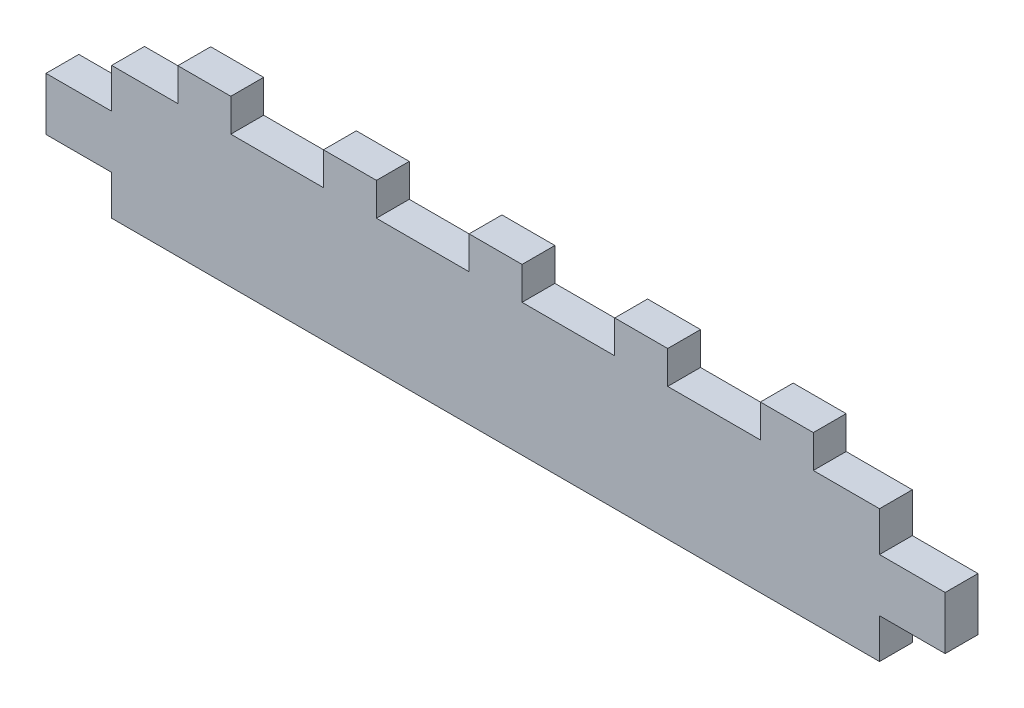
SolidWorks part; units mm, degrees
ref_plane "Front Plane" through (0, 0, 0) normal (0, 0, 1) x (1, 0, 0)
ref_plane "Top Plane" through (0, 0, 0) normal (0, 1, 0) x (1, 0, 0)
ref_plane "Right Plane" through (0, 0, 0) normal (1, 0, 0) x (0, 0, -1)
sketch "Model" plane through (0, 0, 0) normal (0, 0, 1) x (1, 0, 0)
  line L0 (145, 35) -> (145, 50)
  line L1 (-145, 0) -> (145, 0)
  line L2 (-145, 0) -> (-145, 15)
  line L3 (-145, 50) -> (-120, 50)
  line L4 (145, 0) -> (145, 15)
  line L5 (145, 15) -> (169.8, 15)
  line L6 (-145, 35) -> (-145, 50)
  line L7 (145, 35) -> (169.8, 35)
  line L8 (169.8, 15) -> (169.8, 35)
  line L9 (-145, 15) -> (-169.8, 15)
  line L10 (0, 0) -> (0, 62.4) construction
  line L11 (-145, 35) -> (-169.8, 35)
  line L12 (-169.8, 15) -> (-169.8, 35)
  line L13 (10, 50) -> (45, 50)
  line L14 (10, 62.4) -> (-10, 62.4)
  line L15 (10, 62.4) -> (10, 50)
  line L16 (65, 62.4) -> (45, 62.4)
  line L17 (-10, 62.4) -> (-10, 50)
  line L18 (10, 62.4) -> (-10, 50) construction
  line L19 (10, 50) -> (-10, 62.4) construction
  line L20 (65, 62.4) -> (65, 50)
  line L21 (45, 62.4) -> (45, 50)
  line L22 (65, 62.4) -> (45, 50) construction
  line L23 (65, 50) -> (45, 62.4) construction
  line L24 (120, 62.4) -> (100, 62.4)
  line L25 (120, 62.4) -> (120, 50)
  line L26 (100, 62.4) -> (100, 50)
  line L27 (120, 62.4) -> (100, 50) construction
  line L28 (120, 50) -> (100, 62.4) construction
  line L29 (65, 50) -> (100, 50)
  line L30 (120, 50) -> (145, 50)
  line L31 (-45, 62.4) -> (-65, 62.4)
  line L32 (-45, 62.4) -> (-45, 50)
  line L33 (-65, 62.4) -> (-65, 50)
  line L34 (-45, 62.4) -> (-65, 50) construction
  line L35 (-45, 50) -> (-65, 62.4) construction
  line L36 (-100, 62.4) -> (-120, 62.4)
  line L37 (-100, 62.4) -> (-100, 50)
  line L38 (-120, 62.4) -> (-120, 50)
  line L39 (-100, 62.4) -> (-120, 50) construction
  line L40 (-100, 50) -> (-120, 62.4) construction
  line L41 (-45, 50) -> (-10, 50)
  line L42 (-100, 50) -> (-65, 50)
  point P14 (0, 56.2)
  point P20 (55, 56.2)
  point P25 (110, 56.2)
  point P30 (-55, 56.2)
  point P35 (-110, 56.2)
  dimension "D2" = 24.8
  dimension "D4" = 20
  dimension "D6" = 50
  dimension "D8" = 290
  dimension "D10" = 20
  dimension "D12" = 12.4
  dimension "D15" = 35
  dimension "D17" = 35
  dimension "D13" = 3
  dimension "D16" = 3
extrude "Boss-Extrude1" add sketch "Model" along normal blind 12.4
equation "\"tab-width-small\"= 20mm ' Width of the small version of the Tab"
equation "\"baseplate-width\"= 290mm"
equation "\"material-thickness\"= 12.4mm"
equation "\"D2@Model\"=\"material-thickness\" * 2"
equation "\"D12@Model\"=\"material-thickness\""
equation "\"D1@Boss-Extrude1\"=\"material-thickness\""
equation "\"D8@Model\"=\"baseplate-width\""
equation "\"D4@Model\"=\"tab-width-small\""
equation "\"D10@Model\"=\"tab-width-small\""
